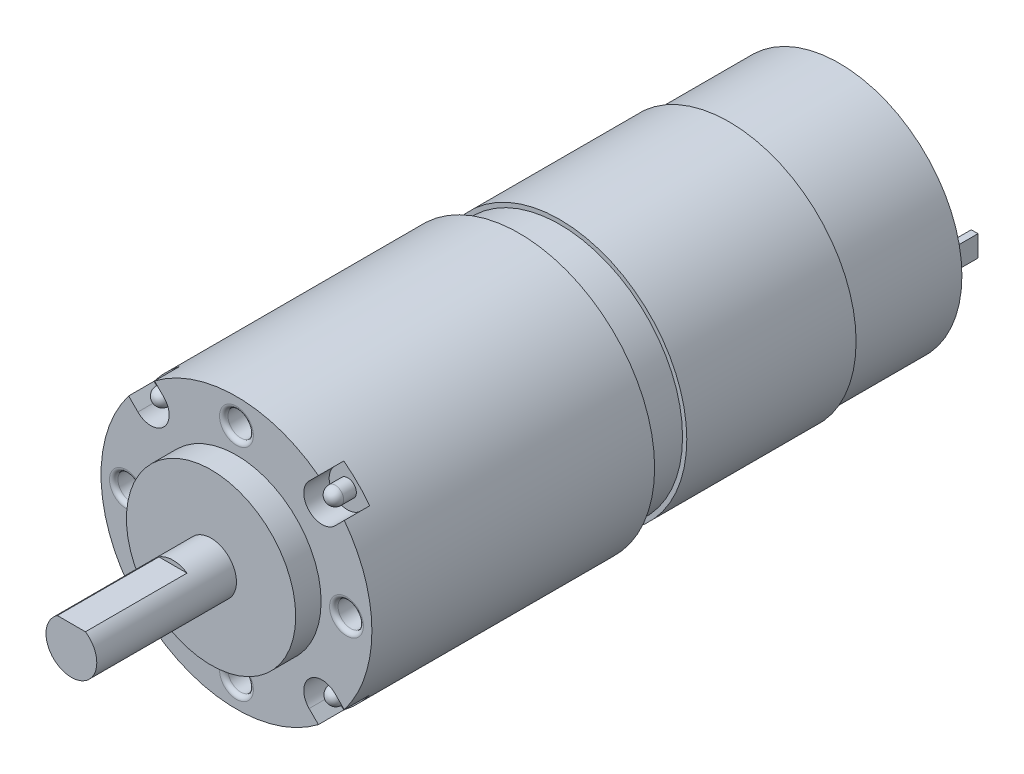
SolidWorks part; units mm, degrees
ref_plane "Plan de face" through (0, 0, 0) normal (0, 0, 1) x (1, 0, 0)
ref_plane "Plan de dessus" through (0, 0, 0) normal (0, 1, 0) x (1, 0, 0)
ref_plane "Plan de droite" through (0, 0, 0) normal (1, 0, 0) x (0, 0, -1)
sketch "Esquisse1" plane through (0, 0, 0) normal (1, 0, 0) x (0, 0, -1)
  line L0 (-20.6, 0) -> (61.7739, 0) construction
  line L1 (61.7739, 0) -> (61.7739, 3.8844)
  line L2 (61.7739, 3.8844) -> (59.7739, 3.8844)
  line L3 (59.7739, 3.8844) -> (59.7739, 14.5)
  line L4 (22.9739, 14.5) -> (26.7739, 14.5)
  line L5 (-11.4261, 16) -> (21.9739, 16)
  line L6 (-30.9261, 3) -> (-30.9261, 0)
  line L7 (21.9739, 14.5) -> (21.9739, 16)
  line L8 (21.9739, 16) -> (-11.4261, 16)
  line L9 (-11.4261, 16) -> (-11.4261, 10)
  line L10 (-11.4261, 10) -> (-14.4261, 10)
  line L11 (-14.4261, 10) -> (-14.4261, 3)
  line L12 (-14.4261, 3) -> (-30.9261, 3)
  line L13 (26.7739, 14.5) -> (26.7739, 15)
  line L14 (26.7739, 15) -> (46.7739, 15)
  line L15 (46.7739, 15) -> (46.7739, 14.5)
  line L16 (46.7739, 14.5) -> (59.7739, 14.5)
  line L17 (-30.9261, 0) -> (61.7739, 0)
  line L18 (61.7739, 0) -> (61.847, -0.5684)
  line L19 (21.9739, 13.5) -> (21.9739, 12.8615)
  line L20 (21.9739, 14.5) -> (21.9739, 13.5)
  line L21 (21.9739, 13.5) -> (21.9655, 13.4905)
  arc A0 (21.9739, 13.5) -> (22.9739, 14.5) centre (22.9739, 13.5) cw
  dimension "D8" = 1
  dimension "D1" = 15
  dimension "D2" = 10
  dimension "D3" = 16
  dimension "D4" = 14.5
  dimension "D5" = 14.5
  dimension "D6" = 20
  dimension "D7" = 13
  dimension "D9" = 3
  dimension "D10" = 16.5
  dimension "D11" = 3
  dimension "D12" = 33.4
  dimension "D13" = 2
  dimension "D14" = 37.8
revolve "Révolution1" add sketch "Esquisse1" angle 360 about L0
sketch "Esquisse2" plane through (0, 0, 30.9261) normal (0, 0, 1) x (1, 0, 0)
  line L0 (-1.6583, 2.5) -> (1.6583, 2.5)
  line L1 (0, 0) -> (0, 4.855) construction
  arc A0 (1.6583, 2.5) -> (-1.6583, 2.5) centre (0, 0) ccw
  point P5 (0, 2.5)
  point P7 (0, 3)
  dimension "D1" = 0.5
extrude "Enlèv. mat.-Extru.1" cut sketch "Esquisse2" against normal blind 12
sketch "Esquisse3" plane through (0, 0, -59.7739) normal (0, 0, -1) x (-1, 0, 0)
  line L0 (-12, 0) -> (11.284, 0) construction
  line L1 (0, 0) -> (0, 6.3905) construction
  line L2 (-12.4, -1.25) -> (-11.6, -1.25)
  line L3 (-12.4, -1.25) -> (-12.4, 1.25)
  line L4 (-12.4, 1.25) -> (-11.6, 1.25)
  line L5 (-11.6, -1.25) -> (-11.6, 1.25)
  line L6 (-12.4, -1.25) -> (-11.6, 1.25) construction
  line L7 (-12.4, 1.25) -> (-11.6, -1.25) construction
  line L8 (12.4, -1.25) -> (11.6, -1.25)
  line L9 (12.4, 1.25) -> (11.6, 1.25)
  line L10 (12.4, -1.25) -> (12.4, 1.25)
  line L11 (11.6, -1.25) -> (11.6, 1.25)
  dimension "D1" = 12
  dimension "D2" = 2.5
  dimension "D3" = 0.8
extrude "Boss.-Extru.1" add sketch "Esquisse3" along normal blind 4
sketch "Esquisse4" plane through (0, 0, 11.4261) normal (0, 0, 1) x (1, 0, 0)
  circle A1 centre (13, 0) radius 1.5
  circle A3 centre (0, -13) radius 1.5
  circle A5 centre (-13, 0) radius 1.5
  circle A7 centre (0, 13) radius 1.5
  point P17 (0, 0)
  dimension "D2" = 3
  dimension "D3" = 4
extrude "Enlèv. mat.-Extru.2" cut sketch "Esquisse4" against normal blind 4
fillet "Congé2" radius 0.5 4 edges at (1.5, 13, 11.4261) (-11.5, 0, 11.4261) (1.5, -13, 11.4261) (14.5, 0, 11.4261)
sketch "Esquisse5" plane through (0, 0, 11.4261) normal (0, 0, 1) x (1, 0, 0)
  line L0 (-13, 0) -> (0, 13) construction
  line L1 (0, 0) -> (-13.6057, 13.6057) construction
  line L2 (-10.1123, 10.1123) -> (-12.7098, 12.7098) construction
  line L3 (-11.6412, 8.5834) -> (-14.2388, 11.1809)
  line L4 (-8.5834, 11.6412) -> (-11.1809, 14.2388)
  line L5 (10.1123, 10.1123) -> (12.7098, 12.7098) construction
  line L6 (8.5834, 11.6412) -> (11.1809, 14.2388)
  line L7 (11.6412, 8.5834) -> (14.2388, 11.1809)
  line L8 (10.1123, -10.1123) -> (12.7098, -12.7098) construction
  line L9 (11.6412, -8.5834) -> (14.2388, -11.1809)
  line L10 (8.5834, -11.6412) -> (11.1809, -14.2388)
  line L11 (-10.1123, -10.1123) -> (-12.7098, -12.7098) construction
  line L12 (-8.5834, -11.6412) -> (-11.1809, -14.2388)
  line L13 (-11.6412, -8.5834) -> (-14.2388, -11.1809)
  arc A0 (-11.6412, 8.5834) -> (-8.5834, 11.6412) centre (-10.1123, 10.1123) ccw
  arc A1 (-11.1809, 14.2388) -> (-14.2388, 11.1809) centre (-12.7098, 12.7098) ccw
  arc A2 (8.5834, 11.6412) -> (11.6412, 8.5834) centre (10.1123, 10.1123) ccw
  arc A3 (14.2388, 11.1809) -> (11.1809, 14.2388) centre (12.7098, 12.7098) ccw
  arc A4 (11.6412, -8.5834) -> (8.5834, -11.6412) centre (10.1123, -10.1123) ccw
  arc A5 (11.1809, -14.2388) -> (14.2388, -11.1809) centre (12.7098, -12.7098) ccw
  arc A6 (-8.5834, -11.6412) -> (-11.6412, -8.5834) centre (-10.1123, -10.1123) ccw
  arc A7 (-14.2388, -11.1809) -> (-11.1809, -14.2388) centre (-12.7098, -12.7098) ccw
  point P0 (0, 13)
  point P1 (-13, 0)
  point P6 (-6.5, 6.5)
  point P12 (-11.4111, 11.4111)
  point P22 (11.4111, 11.4111)
  point P29 (11.4111, -11.4111)
  point P36 (-11.4111, -11.4111)
  point P41 (0, 0)
  dimension "D1" = 4
extrude "Enlèv. mat.-Extru.3" cut sketch "Esquisse5" against normal blind 3
sketch "Esquisse6" plane through (0, 0, 8.4261) normal (0, 0, 1) x (1, 0, 0)
  circle A0 centre (-10.2464, 10.1599) radius 1.0056
  circle A1 centre (10.1599, 10.2464) radius 1.0056
  circle A2 centre (10.2464, -10.1599) radius 1.0056
  circle A3 centre (-10.1599, -10.2464) radius 1.0056
  point P12 (0, 0)
  dimension "D1" = 4
extrude "Boss.-Extru.2" add sketch "Esquisse6" along normal blind 2.5
fillet "Congé3" radius 1 4 edges at (-9.1543, -10.2464, 10.9261) (-9.2408, 10.1599, 10.9261) (11.1655, 10.2464, 10.9261) (11.2519, -10.1599, 10.9261)
